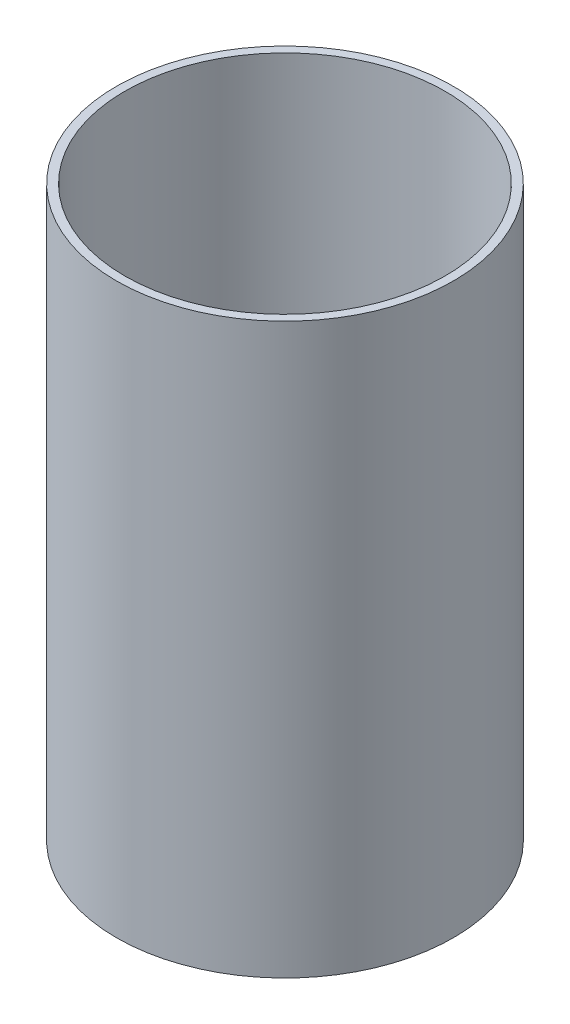
SolidWorks part; units mm, degrees
ref_plane "Front Plane" through (0, 0, 0) normal (0, 0, 1) x (1, 0, 0)
ref_plane "Top Plane" through (0, 0, 0) normal (0, 1, 0) x (1, 0, 0)
ref_plane "Right Plane" through (0, 0, 0) normal (1, 0, 0) x (0, 0, -1)
sketch "Sketch1" plane through (0, 0, 0) normal (0, 1, 0) x (1, 0, 0)
  circle A0 centre (0, 0) radius 38
  circle A1 centre (0, 0) radius 40
  dimension "D1" = 80
  dimension "D2" = 2
extrude "Boss-Extrude1" add sketch "Sketch1" along normal blind 135
